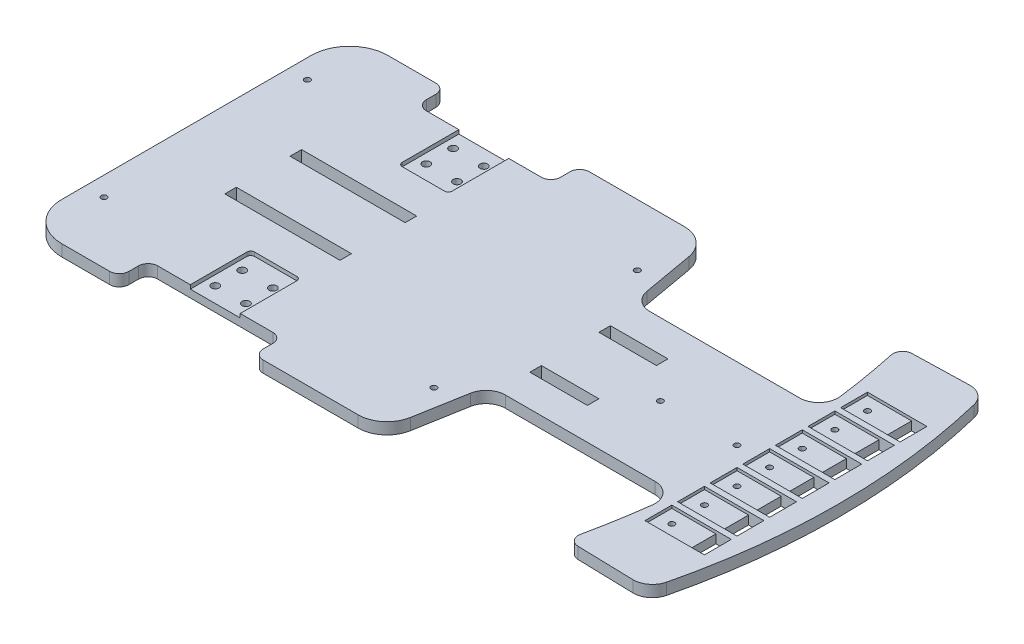
SolidWorks part; units mm, degrees
material "PMMA"
ref_plane "Front Plane" through (0, 0, 0) normal (0, 0, 1) x (1, 0, 0)
ref_plane "Top Plane" through (0, 0, 0) normal (0, 1, 0) x (1, 0, 0)
ref_plane "Right Plane" through (0, 0, 0) normal (1, 0, 0) x (0, 0, -1)
other "Center of Mass"
sketch "Sketch1" plane through (0, 0, 0) normal (0, 1, 0) x (1, 0, 0)
  line L0 (0, 85) -> (-90, 85)
  line L1 (20, 0) -> (50, 0)
  line L2 (0, 20) -> (0, 150)
  line L3 (20, 170) -> (50, 170)
  line L5 (50, 155) -> (120, 155)
  line L7 (50, 0) -> (50, 15)
  line L8 (50, 15) -> (120, 15)
  line L9 (120, 0) -> (120, 15)
  line L10 (120, 170) -> (120, 155)
  line L12 (50, 170) -> (50, 155)
  line L13 (120, 170) -> (174.5163, 170)
  line L14 (120, 0) -> (174.5163, 0)
  line L16 (227.4807, 167.322) -> (275.4798, 122.6739)
  line L19 (285.071, 171.8718) -> (328.4144, 173)
  line L20 (285.071, -1.8718) -> (328.4144, -3)
  line L21 (275.4798, 47.3261) -> (203.8632, 47.3261)
  line L22 (275.4798, 47.3261) -> (281.9573, 47.3261)
  line L23 (194.0167, 39.0714) -> (189.2861, 12.3821)
  line L24 (194.0167, 130.9286) -> (189.2861, 157.6179)
  line L25 (275.4798, 122.6739) -> (203.8632, 122.6739)
  line L26 (275.4798, 122.6739) -> (281.9573, 122.6739)
  arc A2 (330.1629, 3.806) -> (330.1629, 166.194) centre (0, 85) ccw
  arc A3 (287.0212, 7.0253) -> (291.8761, 36.0548) centre (-90, 85) ccw
  arc A4 (292.2185, 131.1958) -> (287.0212, 162.9747) centre (-90, 85) ccw
  circle A8 centre (77, 23) radius 2
  circle A9 centre (93, 23) radius 2
  circle A10 centre (93, 37) radius 2
  circle A11 centre (77, 37) radius 2
  circle A12 centre (93, 147) radius 2
  circle A13 centre (93, 133) radius 2
  circle A14 centre (77, 133) radius 2
  circle A15 centre (77, 147) radius 2
  arc A16 (227.4807, 167.322) -> (220.6699, 170) centre (220.6699, 160) ccw
  arc A24 (20, 170) -> (0, 150) centre (20, 150) ccw
  arc A25 (20, 0) -> (0, 20) centre (20, 20) cw
  arc A26 (330.1629, 3.806) -> (328.4144, 173) centre (0, 85) ccw
  arc A27 (287.0212, 7.0253) -> (291.8761, 36.0548) centre (-90, 85) ccw
  arc A28 (330.1629, 166.194) -> (328.4144, -3) centre (0, 85) cw
  arc A29 (287.0212, 162.9747) -> (292.2185, 131.1958) centre (-90, 85) cw
  arc A30 (292.2185, 131.1958) -> (285.071, 171.8718) centre (-90, 85) ccw
  arc A31 (291.8761, 36.0548) -> (285.071, -1.8718) centre (-90, 85) cw
  arc A32 (281.9573, 47.3261) -> (291.8761, 36.0548) centre (281.9573, 37.3261) cw
  arc A33 (281.9573, 122.6739) -> (291.8761, 133.9452) centre (281.9573, 132.6739) ccw
  arc A34 (194.0167, 39.0714) -> (203.8632, 47.3261) centre (203.8632, 37.3261) cw
  arc A35 (194.0167, 130.9286) -> (203.8632, 122.6739) centre (203.8632, 132.6739) ccw
  arc A36 (189.2861, 12.3821) -> (174.5163, 0) centre (174.5163, 15) cw
  arc A37 (174.5163, 170) -> (189.2861, 157.6179) centre (174.5163, 155) cw
  point P29 (85, 15)
  point P40 (224.6018, 170)
  point P43 (224.6018, 0)
  point P46 (294.4802, 65)
  point P49 (294.4802, 105)
  point P54 (290.6245, 0)
  point P59 (290.6245, 170)
  point P62 (0, 170)
  point P65 (0, 0)
  dimension "D4" = 340
  dimension "D1" = 385
  dimension "D13" = 4
  dimension "D15" = 8
  dimension "D10" = 4
  dimension "D11" = 4
  dimension "D12" = 4
  dimension "D22" = 10
  dimension "D23" = 20
  dimension "D24" = 10
  dimension "D25" = 10
  dimension "D26" = 15
  dimension "D2" = 170
  dimension "D3" = 90
  dimension "D5" = 70
  dimension "D6" = 15
  dimension "D7" = 50
  dimension "D8" = 20
  dimension "D9" = 224.6018
  dimension "D14" = 8
  dimension "D16" = 16
  dimension "D17" = 8
  dimension "D18" = 14
  dimension "D19" = 14
  dimension "D20" = 16
  dimension "D21" = 8
extrude "Boss-Extrude1" add sketch "Sketch1" along normal blind 5 and the other way blind 1
sketch "Sketch3" plane through (0, 5, 0) normal (0, 1, 0) x (1, 0, 0)
  line L0 (0, 85) -> (-10, 85)
  line L5 (230, 70) -> (230, 64)
  line L10 (200, 100) -> (230, 100)
  line L11 (20, 170) -> (50, 170) construction
  line L12 (100, 65) -> (40, 65)
  line L13 (100, 65) -> (100, 71)
  line L14 (100, 71) -> (40, 71)
  line L15 (40, 65) -> (40, 71)
  line L16 (100, 99) -> (40, 99)
  line L17 (100, 99) -> (100, 105)
  line L18 (100, 105) -> (40, 105)
  line L19 (40, 99) -> (40, 105)
  line L20 (20, 0) -> (50, 0) construction
  line L21 (200, 100) -> (200, 106)
  line L22 (200, 106) -> (230, 106)
  line L23 (0, 20) -> (0, 150) construction
  line L24 (230, 100) -> (230, 106)
  line L25 (200, 64) -> (230, 64)
  line L26 (200, 70) -> (200, 64)
  line L27 (200, 70) -> (230, 70)
  line L28 (120, 0) -> (174.5163, 0) construction
  line L29 (320, 92) -> (328, 92)
  line L30 (320, 92) -> (320, 78)
  line L31 (320, 78) -> (328, 78)
  line L32 (328, 92) -> (328, 78)
  line L33 (320, 109) -> (320, 95)
  line L34 (320, 109) -> (328, 109)
  line L35 (328, 109) -> (328, 95)
  line L36 (320, 95) -> (328, 95)
  line L37 (320, 126) -> (320, 112)
  line L38 (320, 126) -> (328, 126)
  line L39 (328, 126) -> (328, 112)
  line L40 (320, 112) -> (328, 112)
  line L41 (320, 143) -> (320, 129)
  line L42 (320, 143) -> (328, 143)
  line L43 (328, 143) -> (328, 129)
  line L44 (320, 129) -> (328, 129)
  line L45 (320, 75) -> (320, 61)
  line L46 (320, 75) -> (328, 75)
  line L47 (328, 75) -> (328, 61)
  line L48 (320, 61) -> (328, 61)
  line L49 (320, 58) -> (320, 44)
  line L50 (320, 58) -> (328, 58)
  line L51 (328, 58) -> (328, 44)
  line L52 (320, 44) -> (328, 44)
  line L53 (320, 41) -> (320, 27)
  line L54 (320, 41) -> (328, 41)
  line L55 (328, 41) -> (328, 27)
  line L56 (320, 27) -> (328, 27)
  line L57 (120, 170) -> (174.5163, 170) construction
  circle A0 centre (304, 85) radius 1.5
  circle A1 centre (304, 102) radius 1.5
  circle A2 centre (304, 119) radius 1.5
  circle A3 centre (304, 136) radius 1.5
  circle A4 centre (304, 68) radius 1.5
  circle A5 centre (304, 51) radius 1.5
  circle A6 centre (304, 34) radius 1.5
  circle A7 centre (10, 32) radius 1.5
  circle A8 centre (182, 32) radius 1.5
  circle A9 centre (182, 138) radius 1.5
  circle A10 centre (10, 138) radius 1.5
  circle A11 centre (247, 85) radius 1.5
  circle A12 centre (287, 85) radius 1.5
  dimension "D2" = 3
  dimension "D17" = 16
  dimension "D18" = 7
  dimension "D25" = 3
  dimension "D26" = 3
  dimension "D27" = 3
  dimension "D28" = 3
  dimension "D29" = 10
  dimension "D30" = 10
  dimension "D31" = 172
  dimension "D32" = 32
  dimension "D33" = 32
  dimension "D34" = 32
  dimension "D35" = 32
  dimension "D36" = 3
  dimension "D37" = 3
  dimension "D38" = 17
  dimension "D39" = 57
  dimension "D40" = 15
  dimension "D41" = 15
  dimension "D3" = 40
  dimension "D4" = 10
  dimension "D5" = 30
  dimension "D6" = 6
  dimension "D7" = 200
  dimension "D8" = 15
  dimension "D9" = 60
  dimension "D10" = 6
  dimension "D11" = 60
  dimension "D12" = 6
  dimension "D13" = 65
  dimension "D14" = 65
  dimension "D15" = 8
  dimension "D16" = 14
  dimension "40" = 40
  dimension "D19" = 320
  dimension "D20" = 78
  dimension "D22" = 3
  dimension "D24" = 3
  dimension "172" = 172
  dimension "D21" = 4
  dimension "D23" = 4
extrude "Cut-Extrude2" cut sketch "Sketch3" against normal through all contours A6 | A5 | L49 L52 L51 L50 | L53 L56 L55 L54 | A4 | A0 | A1 | L33 L36 L35 L34 | L37 L40 L39 L38 | L32 L29 L30 L31 | L45 L48 L47 L46 | L41 L44 L43 L42 | A3 | A2 | A11 | A12 | L13 L12 L15 L14 | L17 L16 L19 L18 | L21 L10 L24 L22 | L5 L25 L26 L27 | A10 | A7 | A9 | A8
fillet "Fillet1" radius 5 1 edges at (285.071, 2, -171.8718)
fillet "Fillet2" radius 10 1 edges at (328.4144, 2, -173)
fillet "Fillet3" radius 5 1 edges at (285.071, 2, 1.8718)
fillet "Fillet4" radius 10 1 edges at (328.4144, 2, 3)
fillet "Fillet5" radius 5 1 edges at (50, 2, -15)
fillet "Fillet6" radius 5 1 edges at (120, 2, -15)
fillet "Fillet7" radius 5 1 edges at (120, 2, -155)
fillet "Fillet8" radius 5 1 edges at (50, 2, -155)
fillet "Fillet9" radius 5 1 edges at (50, 2, -170)
fillet "Fillet10" radius 5 1 edges at (120, 2, -170)
fillet "Fillet11" radius 5 1 edges at (50, 2, 0)
fillet "Fillet12" radius 5 1 edges at (120, 2, 0)
sketch "Sketch4" plane through (0, 5, 0) normal (0, 1, 0) x (1, 0, 0)
  line L0 (55, 15) -> (115, 15) construction
  line L1 (74, 46.5) -> (96, 46.5)
  line L2 (72, 44.5) -> (72, 15)
  line L3 (72, 15) -> (98, 15)
  line L4 (98, 44.5) -> (98, 15)
  line L5 (55, 155) -> (115, 155) construction
  line L6 (72, 155) -> (98, 155)
  line L7 (72, 155) -> (72, 125.5)
  line L8 (74, 123.5) -> (96, 123.5)
  line L9 (98, 155) -> (98, 125.5)
  circle A0 centre (77, 23) radius 2 construction
  circle A1 centre (77, 147) radius 2 construction
  arc A2 (98, 44.5) -> (96, 46.5) centre (96, 44.5) ccw
  arc A3 (72, 44.5) -> (74, 46.5) centre (74, 44.5) cw
  arc A4 (96, 123.5) -> (98, 125.5) centre (96, 125.5) ccw
  arc A5 (72, 125.5) -> (74, 123.5) centre (74, 125.5) ccw
  point P18 (98, 46.5)
  point P21 (72, 46.5)
  point P24 (98, 123.5)
  point P27 (72, 123.5)
  dimension "D5" = 5
  dimension "D7" = 2
  dimension "D1" = 26
  dimension "D2" = 26
  dimension "D3" = 31.5
  dimension "D4" = 31.5
  dimension "D6" = 5
extrude "Cut-Extrude3" cut sketch "Sketch4" against normal blind 2
sketch "Sketch5" plane through (0, 5, 0) normal (0, 1, 0) x (1, 0, 0)
  line L0 (320, 44) -> (320, 58)
  line L1 (320, 27) -> (297, 27)
  line L2 (320, 27) -> (320, 41)
  line L3 (320, 41) -> (297, 41)
  line L4 (297, 27) -> (297, 41)
  line L5 (320, 44) -> (297, 44)
  line L6 (297, 44) -> (297, 58)
  line L7 (320, 58) -> (297, 58)
  line L8 (320, 61) -> (320, 75)
  line L9 (320, 61) -> (297, 61)
  line L10 (297, 61) -> (297, 75)
  line L11 (320, 75) -> (297, 75)
  line L12 (320, 78) -> (320, 92)
  line L13 (320, 78) -> (297, 78)
  line L14 (297, 78) -> (297, 92)
  line L15 (320, 92) -> (297, 92)
  line L16 (320, 95) -> (320, 109)
  line L17 (320, 95) -> (297, 95)
  line L18 (297, 95) -> (297, 109)
  line L19 (320, 109) -> (297, 109)
  line L20 (320, 112) -> (320, 126)
  line L21 (320, 112) -> (297, 112)
  line L22 (297, 112) -> (297, 126)
  line L23 (320, 126) -> (297, 126)
  line L24 (320, 129) -> (320, 143)
  line L25 (320, 129) -> (297, 129)
  line L26 (297, 129) -> (297, 143)
  line L27 (320, 143) -> (297, 143)
  dimension "D1" = 23
  dimension "D2" = 14
  dimension "D4" = 17
  dimension "D3" = 7
extrude "Cut-Extrude4" cut sketch "Sketch5" against normal blind 1.5
